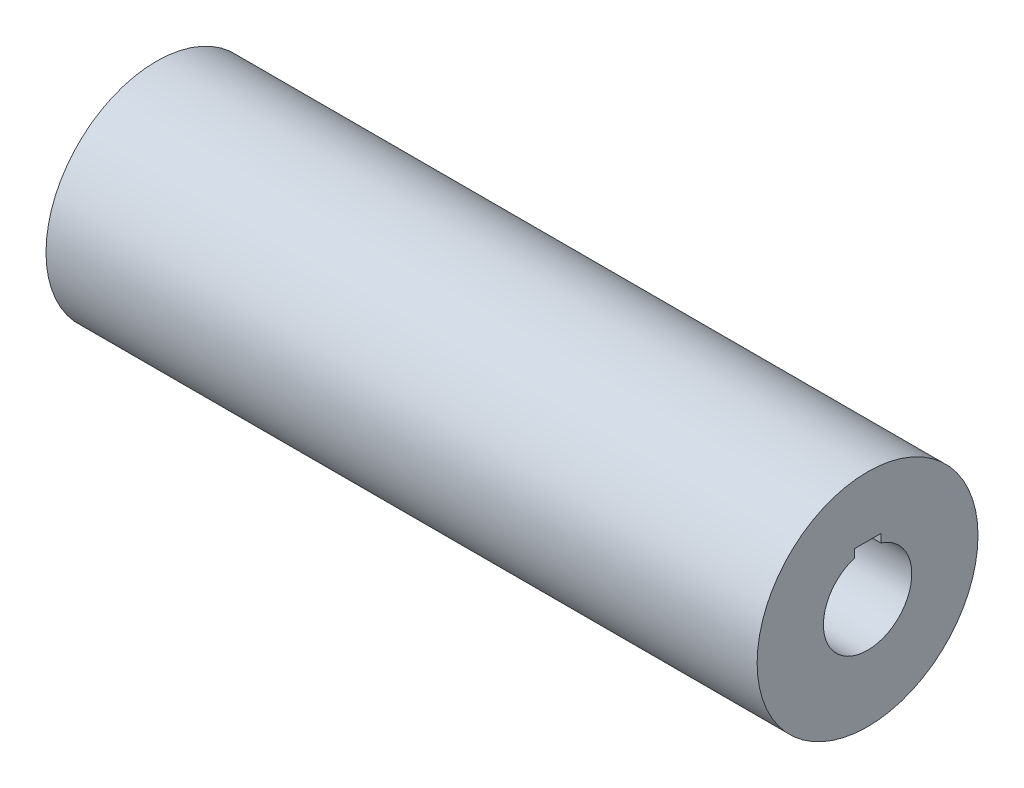
SolidWorks part; units mm, degrees
ref_plane "Ön Düzlem" through (0, 0, 0) normal (0, 0, 1) x (1, 0, 0)
ref_plane "Üst Düzlem" through (0, 0, 0) normal (0, 1, 0) x (1, 0, 0)
ref_plane "Sağ Düzlem" through (0, 0, 0) normal (1, 0, 0) x (0, 0, -1)
sketch "Sketch1" plane through (0, 0, 0) normal (1, 0, 0) x (0, 0, -1)
  circle A0 centre (0, 0) radius 10
  circle A1 centre (0, 0) radius 25
  dimension "D1" = 20
  dimension "D2" = 50
extrude "Boss-Extrude1" add sketch "Sketch1" along normal mid plane 161
sketch "Sketch3" plane through (0, 0, 0) normal (1, 0, 0) x (0, 0, -1)
  line L1 (-3, 8.6) -> (3, 8.6)
  line L2 (-3, 8.6) -> (-3, 11.4)
  line L3 (-3, 11.4) -> (3, 11.4)
  line L4 (3, 8.6) -> (3, 11.4)
  line L5 (-3, 8.6) -> (3, 11.4) construction
  line L6 (-3, 11.4) -> (3, 8.6) construction
  circle A0 centre (0, 0) radius 10 construction
  point P0 (0, 10)
  dimension "D1" = 6
  dimension "D2" = 2.8
extrude "Cut-Extrude1" cut sketch "Sketch3" against normal mid plane 161
